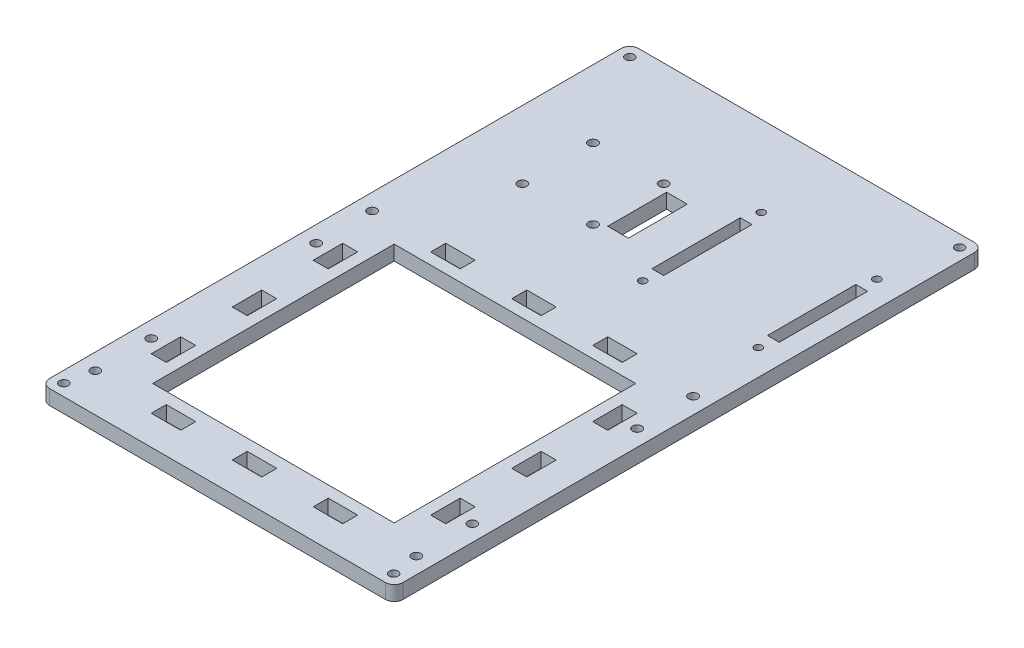
SolidWorks part; units mm, degrees
ref_plane "Front Plane" through (0, 0, 0) normal (0, 0, 1) x (1, 0, 0)
ref_plane "Top Plane" through (0, 0, 0) normal (0, 1, 0) x (1, 0, 0)
ref_plane "Right Plane" through (0, 0, 0) normal (1, 0, 0) x (0, 0, -1)
sketch "Sketch1" plane through (0, 0, 0) normal (0, 1, 0) x (1, 0, 0)
  line L1 (-60, -100) -> (60, -100)
  line L2 (-60, -100) -> (-60, 100)
  line L3 (-60, 100) -> (60, 100)
  line L4 (60, -100) -> (60, 100)
  line L5 (-60, -100) -> (60, 100) construction
  line L6 (-60, 100) -> (60, -100) construction
  circle A0 centre (-56, 96) radius 1.5
  circle A1 centre (56, 96) radius 1.5
  circle A2 centre (55.8222, -96) radius 1.5
  circle A3 centre (-56.1778, -96) radius 1.5
  point P0 (0, 0)
  dimension "D7" = 3
  dimension "D8" = 4
  dimension "D1" = 120
  dimension "D2" = 200
  dimension "D9" = 2
  dimension "D16" = 4
  dimension "D18" = 4
  dimension "D19" = 4
  dimension "D10" = 2
extrude "Boss-Extrude1" add sketch "Sketch1" along normal blind 5
sketch "Sketch3" plane through (0, 5, 0) normal (0, 1, 0) x (1, 0, 0)
  line L0 (60, -100) -> (60, 100) construction
  line L1 (-10, 95) -> (50, 95)
  line L2 (-10, 95) -> (-10, 15)
  line L3 (-10, 15) -> (50, 15)
  line L4 (50, 95) -> (50, 15)
  line L5 (-60, 100) -> (60, 100) construction
  dimension "D1" = 80
  dimension "D2" = 60
  dimension "D3" = 10
  dimension "D4" = 5
extrude "Boss-Extrude2" [suppressed] add sketch "Sketch3" along normal blind 5
sketch "Sketch4" plane through (0, 5, 0) normal (0, 1, 0) x (1, 0, 0)
  line L0 (-60, -100) -> (60, -100) construction
  line L6 (-50, -40) -> (-60, -40) construction
  line L7 (-22.5, 10) -> (-5, 10)
  line L8 (50, -40) -> (60, -40) construction
  line L9 (-32.5, 10) -> (-22.5, 10)
  line L10 (-32.5, 10) -> (-32.5, 4.9)
  line L11 (-32.5, 4.9) -> (-22.5, 4.9)
  line L12 (-22.5, 10) -> (-22.5, 4.9)
  line L13 (-5, 10) -> (5, 10)
  line L14 (-5, 10) -> (-5, 4.9)
  line L15 (-5, 4.9) -> (5, 4.9)
  line L16 (5, 10) -> (5, 4.9)
  line L17 (22.5, 10) -> (32.5, 10)
  line L18 (22.5, 10) -> (22.5, 4.9)
  line L19 (22.5, 4.9) -> (32.5, 4.9)
  line L20 (32.5, 10) -> (32.5, 4.9)
  line L21 (60, -100) -> (60, 100) construction
  line L22 (-32.5, -84.9) -> (-32.5, -90)
  line L23 (-50, -7.5) -> (-44.9, -7.5)
  line L24 (-50, -7.5) -> (-50, -17.5)
  line L25 (-50, -17.5) -> (-44.9, -17.5)
  line L26 (-44.9, -7.5) -> (-44.9, -17.5)
  line L27 (-50, -35) -> (-44.9, -35)
  line L28 (-50, -35) -> (-50, -45)
  line L29 (-50, -45) -> (-44.9, -45)
  line L30 (-44.9, -35) -> (-44.9, -45)
  line L31 (-50, -62.5) -> (-44.9, -62.5)
  line L32 (-50, -62.5) -> (-50, -72.5)
  line L33 (-50, -72.5) -> (-44.9, -72.5)
  line L34 (-44.9, -62.5) -> (-44.9, -72.5)
  line L35 (-32.5, -84.9) -> (-22.5, -84.9)
  line L36 (-22.5, -84.9) -> (-22.5, -90)
  line L37 (-32.5, -90) -> (-22.5, -90)
  line L38 (-5, -84.9) -> (-5, -90)
  line L39 (-5, -84.9) -> (5, -84.9)
  line L40 (5, -84.9) -> (5, -90)
  line L41 (-5, -90) -> (5, -90)
  line L42 (22.5, -84.9) -> (22.5, -90)
  line L43 (22.5, -84.9) -> (32.5, -84.9)
  line L44 (32.5, -84.9) -> (32.5, -90)
  line L45 (22.5, -90) -> (32.5, -90)
  line L46 (44.9, -7.5) -> (44.9, -17.5)
  line L47 (44.9, -7.5) -> (50, -7.5)
  line L48 (50, -7.5) -> (50, -17.5)
  line L49 (44.9, -17.5) -> (50, -17.5)
  line L50 (44.9, -35) -> (44.9, -45)
  line L51 (44.9, -35) -> (50, -35)
  line L52 (50, -35) -> (50, -45)
  line L53 (44.9, -45) -> (50, -45)
  line L54 (44.9, -62.5) -> (44.9, -72.5)
  line L55 (44.9, -62.5) -> (50, -62.5)
  line L56 (50, -62.5) -> (50, -72.5)
  line L57 (44.9, -72.5) -> (50, -72.5)
  line L58 (5, 10) -> (22.5, 10)
  line L59 (-47.45, -17.5) -> (-47.45, -35) construction
  line L60 (-47.45, -45) -> (-47.45, -62.5) construction
  line L61 (-22.5, -87.45) -> (-7.5, -87.45) construction
  line L62 (5, -87.45) -> (20, -87.45) construction
  line L63 (47.45, -62.5) -> (47.45, -45) construction
  line L64 (47.45, -17.5) -> (47.45, -35) construction
  line L65 (32.5, 10) -> (50, 10)
  line L66 (50, 10) -> (50, -7.5)
  line L67 (50, -17.5) -> (50, -35)
  line L68 (50, -45) -> (50, -62.5)
  line L69 (50, -72.5) -> (50, -90)
  line L70 (50, -90) -> (32.5, -90)
  line L71 (22.5, -90) -> (5, -90)
  line L72 (-5, -90) -> (-22.5, -90)
  line L73 (-32.5, -90) -> (-50, -90)
  line L74 (-50, -90) -> (-50, -72.5)
  line L75 (-50, -62.5) -> (-50, -45)
  line L76 (-50, -35) -> (-50, -17.5)
  line L77 (-50, -7.5) -> (-50, 10)
  line L78 (-50, 10) -> (-32.5, 10)
  line L79 (-60, -100) -> (-60, 100) construction
  line L80 (-41, 1) -> (41, 1)
  line L81 (-41, 1) -> (-41, -81)
  line L82 (-41, -81) -> (41, -81)
  line L83 (41, 1) -> (41, -81)
  dimension "D3" = 100
  dimension "D4" = 100
  dimension "D5" = 10
  dimension "D6" = 10
  dimension "D7" = 10
  dimension "D8" = 10
  dimension "D9" = 82
  dimension "D10" = 82
  dimension "D11" = 5.1
  dimension "D12" = 5.1
  dimension "D13" = 5.1
  dimension "D14" = 10
  dimension "D15" = 10
  dimension "D16" = 10
  dimension "D17" = 3.9
  dimension "D18" = 3.9
  dimension "D20" = 5.1
  dimension "D21" = 2
  dimension "D22" = 2
extrude "Cut-Extrude1" cut sketch "Sketch4" against normal up to next
sketch "Sketch5" plane through (0, 5, 0) normal (0, 1, 0) x (1, 0, 0)
  line L0 (-60, 100) -> (60, 100) construction
  line L1 (-40, 67.5) -> (-10, 67.5)
  line L2 (-40, 67.5) -> (-40, 37.5)
  line L3 (-40, 37.5) -> (-10, 37.5)
  line L4 (-10, 67.5) -> (-10, 37.5)
  line L5 (-60, -100) -> (-60, 100) construction
  line L7 (-10, 62.5) -> (-2.9849, 62.5)
  line L8 (-10, 62.5) -> (-10, 42.5)
  line L9 (-10, 42.5) -> (-2.9849, 42.5)
  line L10 (-2.9849, 62.5) -> (-2.9849, 42.5)
  circle A0 centre (-37, 64.5) radius 1.55
  circle A1 centre (-13, 64.5) radius 1.55
  circle A2 centre (-13, 40.5) radius 1.55
  circle A3 centre (-37, 40.5) radius 1.55
  dimension "D3" = 3.1
  dimension "D1" = 30
  dimension "D2" = 30
  dimension "D4" = 3
  dimension "D5" = 3
  dimension "D8" = 32.5
  dimension "D9" = 20
  dimension "D10" = 20
  dimension "D11" = 5
  dimension "D6" = 2
  dimension "D7" = 2
extrude "Cut-Extrude3" cut sketch "Sketch5" against normal through all contours A2 | A3 | A0 | A1 | L8 L7 L10 L9
sketch "Sketch6" plane through (0, 5, 0) normal (0, 1, 0) x (1, 0, 0)
  line L0 (-60, 100) -> (60, 100) construction
  line L1 (10, 74.125) -> (53.25, 74.125)
  line L2 (10, 74.125) -> (10, 30.875)
  line L3 (10, 30.875) -> (53.25, 30.875)
  line L4 (53.25, 74.125) -> (53.25, 30.875)
  line L5 (60, -100) -> (60, 100) construction
  line L6 (14, 67.5) -> (14, 37.5)
  line L7 (53.25, 67.5) -> (49.25, 67.5)
  line L8 (53.25, 67.5) -> (53.25, 37.5)
  line L9 (53.25, 37.5) -> (49.25, 37.5)
  line L10 (49.25, 67.5) -> (49.25, 37.5)
  line L11 (14, 67.5) -> (10, 67.5)
  line L12 (10, 67.5) -> (10, 37.5)
  line L13 (14, 37.5) -> (10, 37.5)
  circle A0 centre (51.25, 72.625) radius 1.3
  circle A1 centre (12, 72.625) radius 1.3
  circle A2 centre (12, 32.375) radius 1.3
  circle A3 centre (51.25, 32.375) radius 1.3
  dimension "D5" = 2.6
  dimension "D1" = 43.25
  dimension "D2" = 43.25
  dimension "D3" = 25.875
  dimension "D4" = 6.75
  dimension "D6" = 2
  dimension "D7" = 1.5
  dimension "D10" = 30
  dimension "D11" = 6.625
  dimension "D12" = 4
  dimension "D8" = 2
  dimension "D9" = 2
  dimension "D13" = 2
extrude "Cut-Extrude5" cut sketch "Sketch6" against normal blind 10 contours L13 L6 L11 L2 | L7 L10 L9 L4 | A0 | A1 | A2 | A3
sketch "Sketch7" plane through (0, 5, 0) normal (0, 1, 0) x (1, 0, 0)
  line L0 (-32.5, 10) -> (-32.5, 4.9) construction
  line L1 (-57.5, 10) -> (-32.5, 10)
  line L2 (-57.5, 10) -> (-57.5, -15)
  line L3 (-57.5, -15) -> (-32.5, -15)
  line L4 (-32.5, 10) -> (-32.5, -15)
  line L5 (-32.5, 10) -> (-22.5, 10) construction
  line L6 (0, 1) -> (0, -81) construction
  line L7 (-41, 1) -> (41, 1) construction
  line L8 (-41, -81) -> (41, -81) construction
  line L9 (-41, -40) -> (41, -40) construction
  line L10 (-41, 1) -> (-41, -81) construction
  line L11 (41, 1) -> (41, -81) construction
  circle A0 centre (-54.5, 7) radius 1.55
  circle A1 centre (-54.5, -12) radius 1.55
  circle A2 centre (-54.5, -68) radius 1.55
  circle A3 centre (-54.5, -87) radius 1.55
  circle A4 centre (54.5, -12) radius 1.55
  circle A5 centre (54.5, 7) radius 1.55
  circle A6 centre (54.5, -87) radius 1.55
  circle A7 centre (54.5, -68) radius 1.55
  dimension "D3" = 3.1
  dimension "D1" = 25
  dimension "D2" = 25
  dimension "D4" = 3
  dimension "D5" = 3
  dimension "D6" = 2
extrude "Cut-Extrude6" cut sketch "Sketch7" against normal through all contours A1 | A0 | A2 | A3 | A6 | A7 | A4 | A5
fillet "Fillet1" radius 3 4 edges at (60, 2.5, 100) (-60, 2.5, 100) (60, 2.5, -100) (-60, 2.5, -100)
